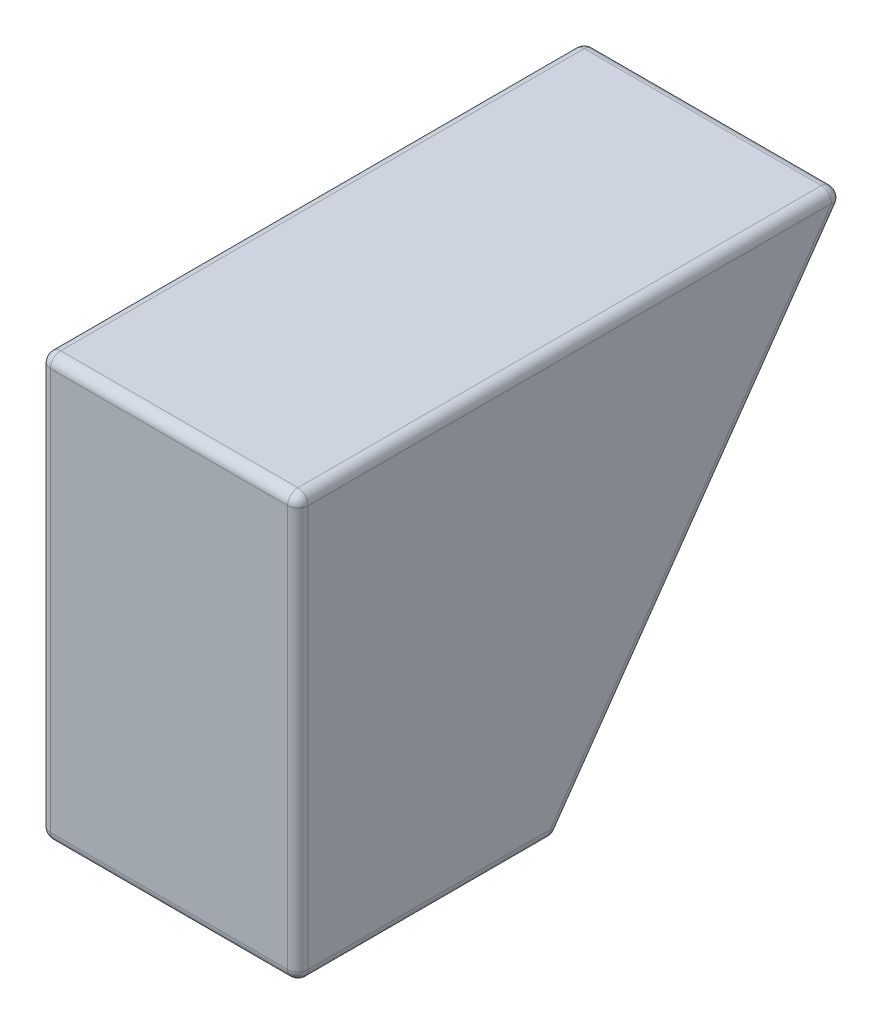
SolidWorks part; units mm, degrees
ref_plane "Front Plane" through (0, 0, 0) normal (0, 0, 1) x (1, 0, 0)
ref_plane "Top Plane" through (0, 0, 0) normal (0, 1, 0) x (1, 0, 0)
ref_plane "Right Plane" through (0, 0, 0) normal (1, 0, 0) x (0, 0, -1)
sketch "Sketch2" plane through (0, 0, 0) normal (1, 0, 0) x (0, 0, -1)
  line L0 (25, 40.9576) -> (53.6788, 40.9576)
  line L1 (53.6788, 40.9576) -> (25, 0)
  line L3 (25, 0) -> (0, 0)
  line L4 (0, 0) -> (0, 40.9576)
  line L5 (0, 40.9576) -> (25, 40.9576)
  point P3 (25, 0)
  point P4 (0, 0)
  point P8 (0, 0)
  point P10 (0, 0)
  dimension "D1" = 50
  dimension "D2" = 25
extrude "Boss-Extrude1" add sketch "Sketch2" along normal blind 25
sketch "Sketch3" plane through (0, 0, 0) normal (0, -1, 0) x (1, 0, 0)
  line L0 (12.5, 0) -> (12.5, -25) construction
  line L1 (25, 0) -> (0, 0) construction
  line L2 (25, -25) -> (0, -25) construction
  line L3 (25, -12.5) -> (0, -12.5) construction
  line L4 (25, 0) -> (25, -25) construction
  line L5 (0, 0) -> (0, -25) construction
  circle A0 centre (12.5, -12.5) radius 5
  dimension "D1" = 10
extrude "Cut-Extrude1" cut sketch "Sketch3" against normal blind 30
ref_plane "Plane1" through (0, 0, -15) normal (0, 0, 1) x (1, 0, 0)
sketch "Sketch8" plane through (0, 0, -15) normal (0, 0, 1) x (1, 0, 0)
  line L0 (25, 5.9576) -> (0, 5.9576) construction
  line L1 (25, 0) -> (25, 40.9576) construction
  line L2 (0, 0) -> (0, 40.9576) construction
  line L3 (25, 40.9576) -> (0, 40.9576) construction
  line L5 (5, 4.4576) -> (20, 4.4576)
  line L6 (5, 4.4576) -> (5, 7.4576)
  line L7 (5, 7.4576) -> (20, 7.4576)
  line L8 (20, 4.4576) -> (20, 7.4576)
  line L9 (5, 4.4576) -> (20, 7.4576) construction
  line L10 (5, 7.4576) -> (20, 4.4576) construction
  point P8 (12.5, 5.9576)
  dimension "D1" = 35
  dimension "D2" = 3
  dimension "D3" = 15
extrude "Cut-Extrude10" cut sketch "Sketch8" against normal blind 30
fillet "Fillet1" radius 1 16 edges at (12.5, 0, 0) (25, 0, -12.5) (25, 20.4788, 0) (12.5, 0, -25) (25, 20.4788, -39.3394) (5, 5.9576, -29.1716) (12.5, 7.4576, -30.2219) (20, 5.9576, -29.1716) (12.5, 4.4576, -28.1212) (0, 0, -12.5) (0, 20.4788, -39.3394) (0, 20.4788, 0) (12.5, 40.9576, -53.6788) (25, 40.9576, -26.8394) (12.5, 40.9576, 0) (0, 40.9576, -26.8394)
fillet "Fillet2" radius 1 1 edges at (12.5, 0, -17.5)
